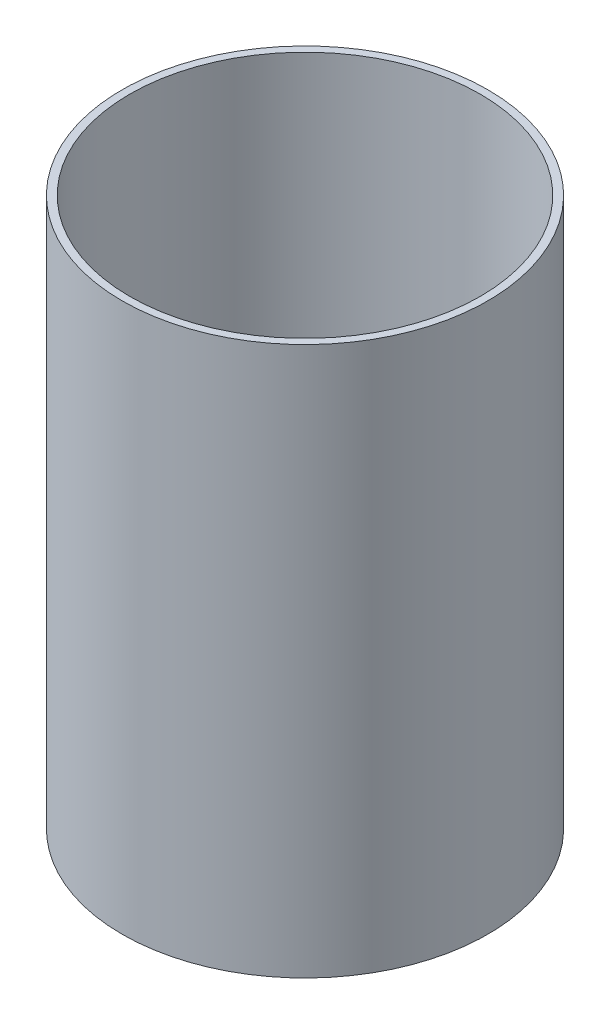
SolidWorks part; units mm, degrees
ref_plane "Front Plane" through (0, 0, 0) normal (0, 0, 1) x (1, 0, 0)
ref_plane "Top Plane" through (0, 0, 0) normal (0, 1, 0) x (1, 0, 0)
ref_plane "Right Plane" through (0, 0, 0) normal (1, 0, 0) x (0, 0, -1)
sketch "Sketch1" plane through (0, 0, 0) normal (0, 1, 0) x (1, 0, 0)
  circle A0 centre (0, 0) radius 146.05
  circle A1 centre (0, 0) radius 152.4
  dimension "D1" = 146.05
  dimension "D2" = 152.4
extrude "Boss-Extrude1" add sketch "Sketch1" along normal blind 457.2
